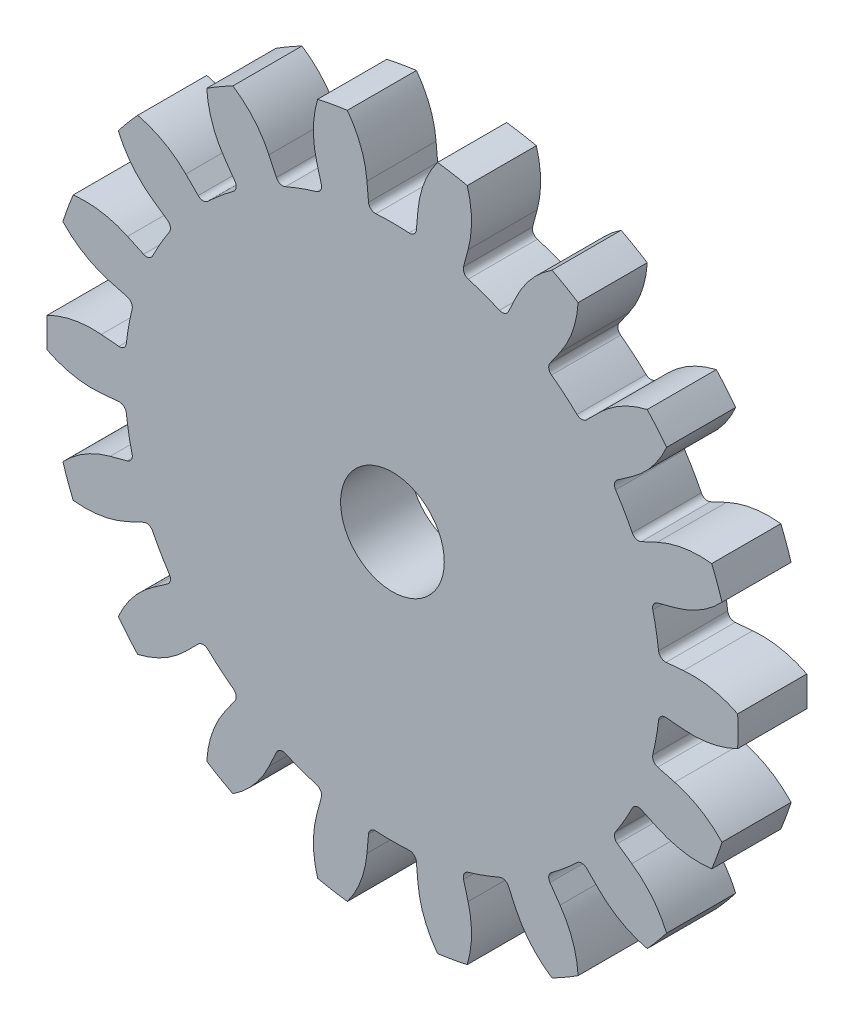
SolidWorks part; units mm, degrees
ref_plane "Front Plane" through (0, 0, 0) normal (0, 0, 1) x (1, 0, 0)
ref_plane "Top Plane" through (0, 0, 0) normal (0, 1, 0) x (1, 0, 0)
ref_plane "Right Plane" through (0, 0, 0) normal (1, 0, 0) x (0, 0, -1)
sketch "Sketch1" plane through (0, 0, 0) normal (0, 0, 1) x (1, 0, 0)
  line L0 (0, 0) -> (69.1291, 0) construction
  line L1 (0, 0) -> (38.1613, 6.7289) construction
  line L2 (0, 0) -> (57.2936, 5.0125) construction
  line L3 (0, 0) -> (50.9515, 2.2246) construction
  line L4 (42.1241, 3.6854) -> (38.6025, 3.3773)
  line L5 (0, 0) -> (38.1613, 6.7289)
  line L6 (42.1241, -3.6854) -> (38.6025, -3.3773)
  line L7 (0, 0) -> (38.1613, -6.7289)
  circle A0 centre (0, 0) radius 38.75 construction
  circle A1 centre (0, 0) radius 42.285 construction
  circle A2 centre (0, 0) radius 50 construction
  arc A3 (42.1241, 3.6854) -> (49.9524, 2.181) centre (43.3938, -10.8274) cw
  arc A4 (38.1613, 6.7289) -> (38.6025, 3.3773) centre (0, 0) cw
  arc A5 (49.9524, 2.181) -> (49.9524, -2.181) centre (0, 0) cw
  arc A6 (42.1241, -3.6854) -> (49.9524, -2.181) centre (43.3938, 10.8274) ccw
  arc A7 (38.1613, -6.7289) -> (38.6025, -3.3773) centre (0, 0) ccw
  dimension "D1" = 100
  dimension "D2" = 84.57
  dimension "D3" = 77.5
  dimension "D4" = 10
  dimension "D5" = 5
  dimension "D6" = 2.5
extrude "Boss-Extrude1" add sketch "Sketch1" along normal blind 10
fillet "Fillet1" radius 1 2 edges at (38.6025, -3.3773, 5) (38.6025, 3.3773, 5)
pattern_circular "CirPattern1" count 18 over 360 about axis through (0, 0, 0) along (0, 0, 1) of "Boss-Extrude1", "Fillet1"
sketch "Sketch2" plane through (0, 0, 10) normal (0, 0, 1) x (1, 0, 0)
  circle A0 centre (0, 0) radius 7.5
  dimension "D1" = 15
extrude "Cut-Extrude1" cut sketch "Sketch2" against normal through all
